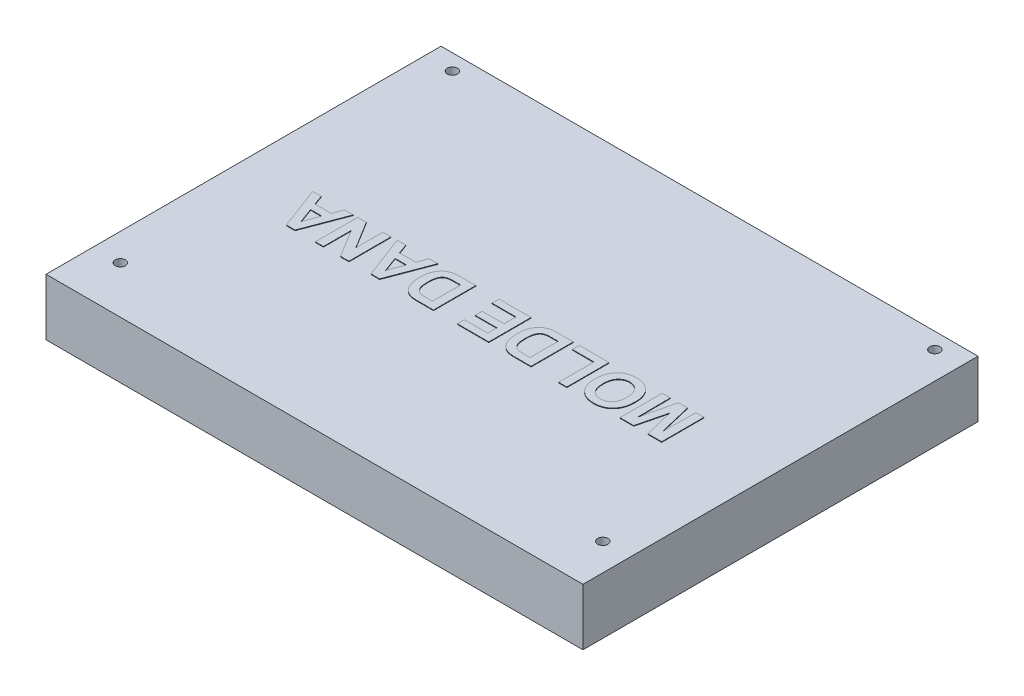
SolidWorks part; units mm, degrees
ref_plane "Alzado" through (0, 0, 0) normal (0, 0, 1) x (1, 0, 0)
ref_plane "Planta" through (0, 0, 0) normal (0, 1, 0) x (1, 0, 0)
ref_plane "Vista lateral" through (0, 0, 0) normal (1, 0, 0) x (0, 0, -1)
sketch "Croquis1" plane through (0, 0, 0) normal (0, 1, 0) x (1, 0, 0)
  line L1 (0, 0) -> (946, 0)
  line L2 (0, 0) -> (0, -696)
  line L3 (0, -696) -> (946, -696)
  line L4 (946, 0) -> (946, -696)
  dimension "D1" = 946
  dimension "D2" = 696
extrude "Saliente-Extruir1" add sketch "Croquis1" along normal blind 100
sketch "Croquis2" plane through (0, 100, 0) normal (0, 1, 0) x (1, 0, 0)
  line L0 (473, 0) -> (473, -696) construction
  line L1 (946, 0) -> (0, 0) construction
  line L2 (0, -696) -> (946, -696) construction
  line L3 (0, -348) -> (946, -348) construction
  line L4 (0, 0) -> (0, -696) construction
  line L5 (946, -696) -> (946, 0) construction
  circle A0 centre (48, -28) radius 9
  circle A1 centre (898, -28) radius 9
  circle A2 centre (48, -613) radius 9
  circle A3 centre (898, -613) radius 9
  dimension "D1" = 18
  dimension "D2" = 18
  dimension "D7" = 18
  dimension "D8" = 18
  dimension "D9" = 425
  dimension "D10" = 425
  dimension "D11" = 320
  dimension "D12" = 320
  dimension "D3" = 425
  dimension "D4" = 265
  dimension "D5" = 425
  dimension "D6" = 265
extrude "Cortar-Extruir1" cut sketch "Croquis2" against normal blind 120
sketch "Croquis3" plane through (0, 100, 0) normal (0, 1, 0) x (1, 0, 0)
  line L0 (805.572, -335.7007) -> (50.8893, -335.7007) construction
  text T0 "MOLDE DANA" font "Arial" height in points 290
extrude "Saliente-Extruir2" add sketch "Croquis3" along normal blind 1
